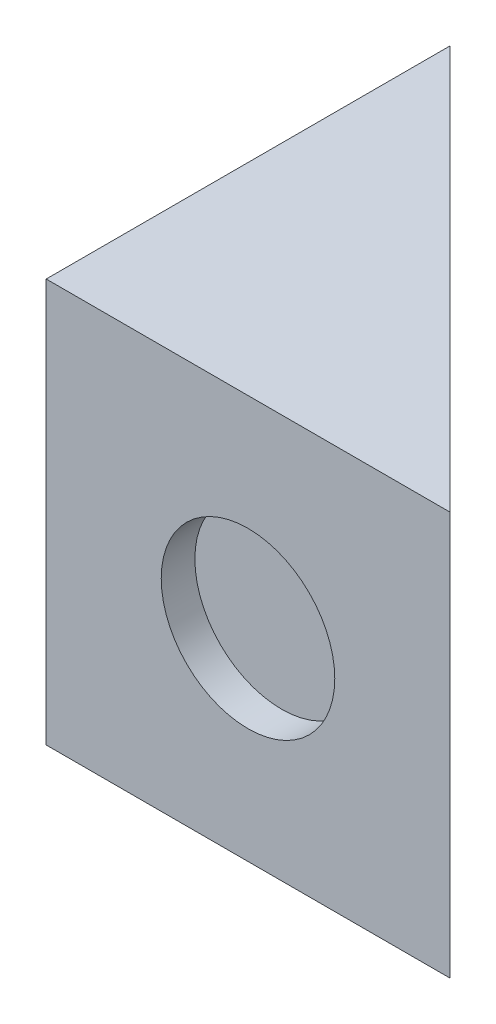
SolidWorks part; units mm, degrees
ref_plane "Front Plane" through (0, 0, 0) normal (0, 0, 1) x (1, 0, 0)
ref_plane "Top Plane" through (0, 0, 0) normal (0, 1, 0) x (1, 0, 0)
ref_plane "Right Plane" through (0, 0, 0) normal (1, 0, 0) x (0, 0, -1)
sketch "Sketch1" plane through (0, 0, 0) normal (0, 1, 0) x (1, 0, 0)
  line L0 (0, 0) -> (0, 38.1)
  line L1 (0, 38.1) -> (38.1, 0)
  line L2 (38.1, 0) -> (0, 0)
  dimension "D1" = 45
  dimension "D2" = 38.1
  dimension "D3" = 38.1
extrude "Boss-Extrude1" add sketch "Sketch1" along normal blind 38.1
sketch "Sketch2" plane through (0, 0, 0) normal (0, 0, 1) x (1, 0, 0)
  line L0 (0, 38.1) -> (38.1, 38.1) construction
  line L1 (0, 38.1) -> (0, 0) construction
  circle A0 centre (19.05, 19.05) radius 8.1915
  dimension "D3" = 16.383
  dimension "D1" = 19.05
  dimension "D2" = 19.05
extrude "Cut-Extrude1" cut sketch "Sketch2" against normal blind 3.175 contours A0
sketch "Sketch3" plane through (0, 0, 0) normal (-1, 0, 0) x (0, 0, 1)
  line L0 (-38.1, 38.1) -> (0, 38.1) construction
  line L1 (-38.1, 38.1) -> (-38.1, 0) construction
  circle A0 centre (-25.4, 19.05) radius 8.1915
  dimension "D3" = 16.383
  dimension "D1" = 19.05
  dimension "D2" = 12.7
extrude "Cut-Extrude2" cut sketch "Sketch3" against normal blind 3.175
sketch "Sketch4" plane through (0, 0, 0) normal (-1, 0, 0) x (0, 0, 1)
  line L0 (-38.1, 38.1) -> (0, 38.1) construction
  line L1 (0, 38.1) -> (0, 0) construction
  circle A0 centre (-7.62, 19.05) radius 4.8895
  dimension "D1" = 9.779
  dimension "D2" = 19.05
  dimension "D3" = 7.62
extrude "Cut-Extrude3" cut sketch "Sketch4" against normal blind 1.6129
